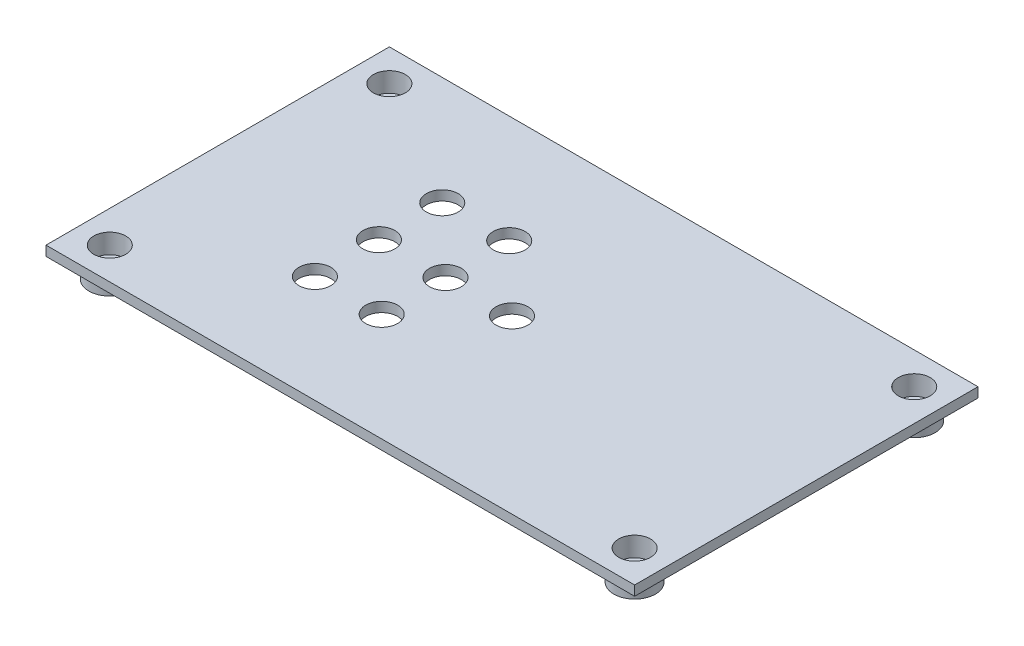
SolidWorks part; units mm, degrees
ref_plane "Front Plane" through (0, 0, 0) normal (0, 0, 1) x (1, 0, 0)
ref_plane "Top Plane" through (0, 0, 0) normal (0, 1, 0) x (1, 0, 0)
ref_plane "Right Plane" through (0, 0, 0) normal (1, 0, 0) x (0, 0, -1)
sketch "Sketch1" plane through (0, 0, 0) normal (0, 1, 0) x (1, 0, 0)
  line L1 (-60, 35) -> (60, 35)
  line L2 (-60, 35) -> (-60, -35)
  line L3 (-60, -35) -> (60, -35)
  line L4 (60, 35) -> (60, -35)
  line L5 (-60, 35) -> (60, -35) construction
  line L6 (-60, -35) -> (60, 35) construction
  point P0 (0, 0)
  dimension "D1" = 120
  dimension "D2" = 70
extrude "Boss-Extrude1" add sketch "Sketch1" along normal blind 2 contours L2 L3 L4 L1
sketch "Sketch3" plane through (0, 2, 0) normal (0, 1, 0) x (1, 0, 0)
  line L2 (60, 35) -> (60, -35) construction
  line L3 (-60, -35) -> (60, -35) construction
  circle A0 centre (-53.5, 28.5) radius 4.25
  circle A1 centre (53.5, 28.5) radius 4.25
  circle A2 centre (-53.5, -28.5) radius 4.25
  circle A3 centre (53.5, -28.5) radius 4.25
  point P0 (-53.5, 28.5)
  point P2 (53.5, 28.5)
  point P3 (53.5, -28.5)
  point P4 (-53.5, -28.5)
  point P9 (0, 0)
  point P20 (0, 0)
  point P21 (-94.4955, 36.9003)
  dimension "D3" = 6.5
  dimension "D4" = 6.5
sketch "Sketch4" plane through (0, 2, 0) normal (0, 1, 0) x (1, 0, 0)
  line L18 (-30.8791, -14.0818) -> (-23.2298, -12.1627) construction
  line L19 (-29.7298, -12.1627) -> (-22.0475, -14.1965) construction
  line L20 (-30.8172, -1.0024) -> (-23.2298, 0.7871) construction
  line L21 (-29.7298, 0.7871) -> (-22.1091, -1.1095) construction
  line L22 (-30.9536, 11.8406) -> (-23.2095, 13.8874) construction
  line L23 (-29.7501, 13.8874) -> (-21.9738, 11.7194) construction
  circle A0 centre (-27.0544, -13.1223) radius 3.25
  circle A1 centre (-27.0235, -0.1076) radius 3.25
  circle A2 centre (-27.0816, 12.864) radius 3.25
  circle A3 centre (-13.5671, 0) radius 3.25
  circle A4 centre (-13.5671, -13) radius 3.25
  circle A5 centre (-13.5671, 13) radius 3.25
  circle A6 centre (0, 0) radius 3.25
  point P0 (-26.5671, -13)
  point P1 (-26.5671, 0)
  point P2 (-26.5671, 13)
  point P3 (-13.5671, -13)
  point P4 (-13.5671, 0)
  point P5 (-13.5671, 13)
  point P6 (0, 0)
  point P7 (-13.5671, 0)
  point P12 (-13.5671, 13)
  point P13 (-13.5671, -13)
  point P22 (-26.5671, -13)
  point P27 (-26.5671, 0)
  point P32 (-26.5671, 13)
  point P37 (0, 0)
  point P40 (0, -13)
  point P41 (0, 13)
sketch "Sketch6" plane through (0, 2, 0) normal (0, 1, 0) x (1, 0, 0)
  circle A0 centre (0, -13) radius 2
  circle A1 centre (0, 13) radius 2
extrude "Boss-Extrude2" add sketch "Sketch6" against normal blind 11
extrude "Cut-Extrude2" cut sketch "Sketch4" against normal blind 11 contours A5 | A3 | A6 | A2 | A1 | A0 | A4
extrude "Boss-Extrude3" add sketch "Sketch3" against normal blind 6
sketch "Sketch8" plane through (0, 2, 0) normal (0, 1, 0) x (1, 0, 0)
  circle A0 centre (-53.5, 28.5) radius 1.75
  circle A1 centre (-53.5, -28.5) radius 1.75
  circle A2 centre (53.5, -28.5) radius 1.75
  circle A3 centre (53.5, 28.5) radius 1.75
extrude "Cut-Extrude6" cut sketch "Sketch8" against normal blind 8
sketch "Sketch9" plane through (0, 2, 0) normal (0, 1, 0) x (1, 0, 0)
  circle A0 centre (-53.5, 28.5) radius 3.25
  circle A1 centre (53.5, 28.5) radius 3.25
  circle A2 centre (-53.5, -28.5) radius 3.25
  circle A3 centre (53.5, -28.5) radius 3.25
extrude "Cut-Extrude8" cut sketch "Sketch9" against normal blind 4
